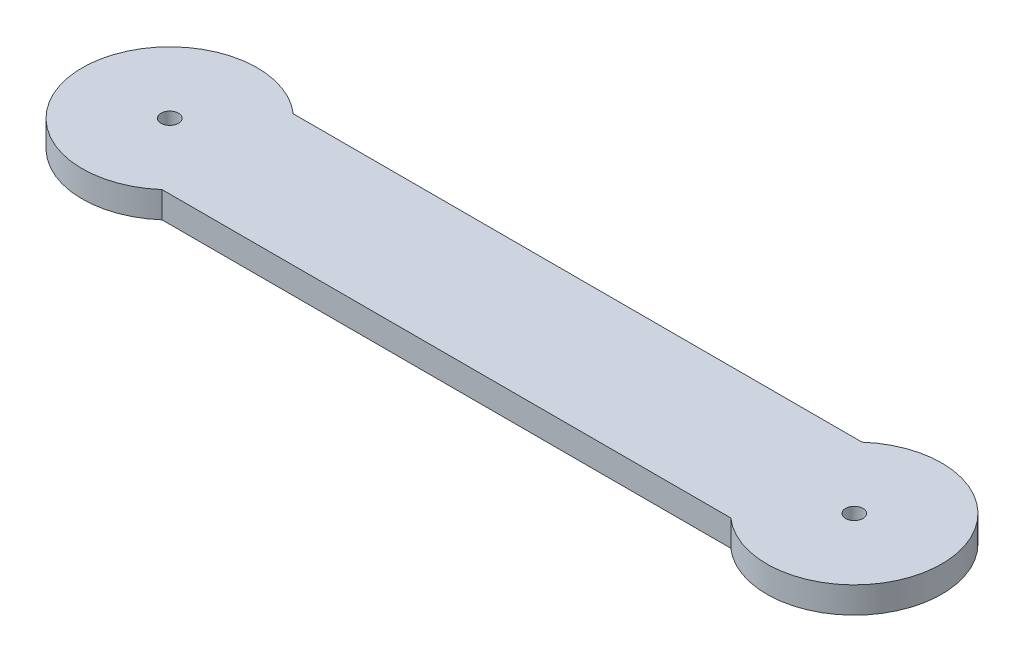
SolidWorks part; units mm, degrees
ref_plane "Front Plane" through (0, 0, 0) normal (0, 0, 1) x (1, 0, 0)
ref_plane "Top Plane" through (0, 0, 0) normal (0, 1, 0) x (1, 0, 0)
ref_plane "Right Plane" through (0, 0, 0) normal (1, 0, 0) x (0, 0, -1)
sketch "Sketch1" plane through (0, 0, 0) normal (0, 1, 0) x (1, 0, 0)
  line L1 (0, 0) -> (-65, 0)
  line L3 (0, 15) -> (-65, 15)
  arc A0 (0, 15) -> (0, 0) centre (6.6144, 7.5) cw
  arc A1 (-65, 15) -> (-65, 0) centre (-71.6144, 7.5) ccw
  dimension "D2" = 10
  dimension "D4" = 10
  dimension "D1" = 15
extrude "Boss-Extrude1" add sketch "Sketch1" along normal blind 3
sketch "Sketch2" plane through (0, 3, 0) normal (0, 1, 0) x (1, 0, 0)
  circle A0 centre (-71.6144, 7.5) radius 1
  circle A1 centre (6.6144, 7.5) radius 1
  dimension "D1" = 2
  dimension "D2" = 2
extrude "Cut-Extrude1" cut sketch "Sketch2" against normal blind 13
